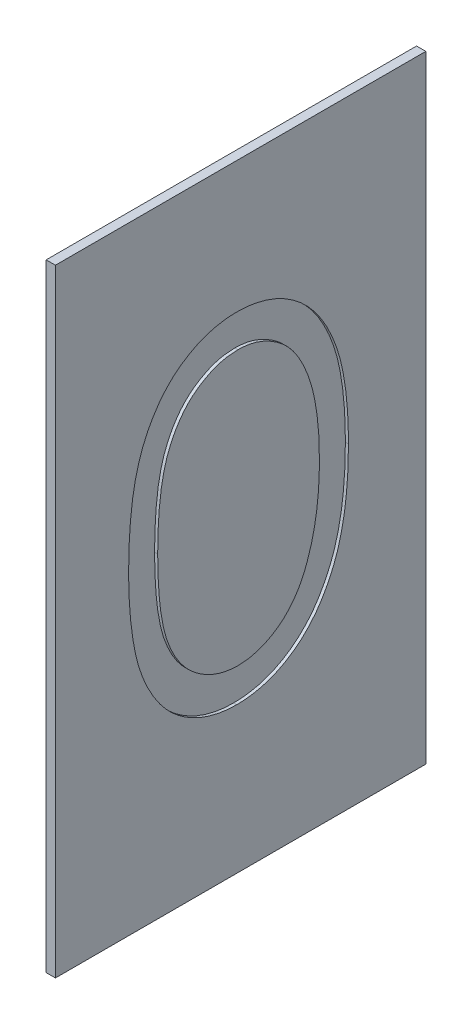
SolidWorks part; units mm, degrees
ref_plane "Front Plane" through (0, 0, 0) normal (0, 0, 1) x (1, 0, 0)
ref_plane "Top Plane" through (0, 0, 0) normal (0, 1, 0) x (1, 0, 0)
ref_plane "Right Plane" through (0, 0, 0) normal (1, 0, 0) x (0, 0, -1)
sketch "Sketch1" plane through (0, 0, 0) normal (1, 0, 0) x (0, 0, -1)
  line L1 (0, 0) -> (60, 0)
  line L2 (0, 0) -> (0, 100)
  line L3 (0, 100) -> (60, 100)
  line L4 (60, 0) -> (60, 100)
  dimension "D1" = 60
  dimension "D2" = 100
extrude "Boss-Extrude1" add sketch "Sketch1" along normal blind 1.5
sketch "Sketch2" plane through (1.5, 0, 0) normal (1, 0, 0) x (0, 0, -1)
  line L0 (0, 25) -> (60, 25) construction
  line L1 (0, 100) -> (0, 0) construction
  line L2 (60, 0) -> (60, 100) construction
  text T0 "0\r\n" font "Century Gothic" height in points 200
  point P7 (0, 0)
  dimension "D1" = 25
extrude "Cut-Extrude1" cut sketch "Sketch2" against normal blind 0.5
